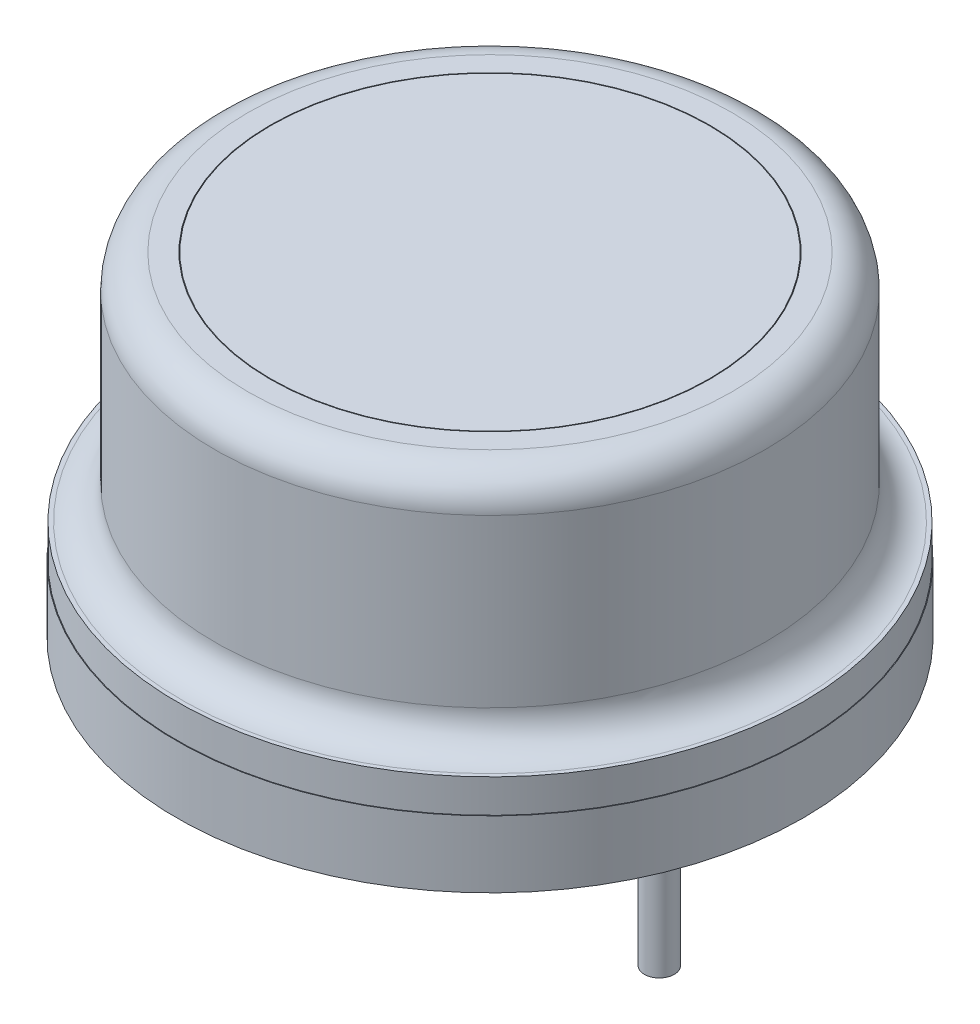
SolidWorks part; units mm, degrees
material "Stainless Steel (ferritic)"
ref_plane "Front" through (0, 0, 0) normal (0, 0, 1) x (1, 0, 0)
ref_plane "Top" through (0, 0, 0) normal (0, 1, 0) x (1, 0, 0)
ref_plane "Right" through (0, 0, 0) normal (1, 0, 0) x (0, 0, -1)
sketch "Sketch1" plane through (0, 0, 0) normal (0, 0, 1) x (1, 0, 0)
  line L0 (0, 0) -> (0, 4.4) construction
  line L1 (0, 4.4) -> (-3.3, 4.4)
  line L2 (-3.3, 4.4) -> (-3.3, 5)
  line L3 (-3.3, 5) -> (-3.63, 5)
  line L4 (-4.13, 4.5) -> (-4.13, 2)
  line L5 (-4.63, 1.5) -> (-4.69, 1.5)
  line L6 (-4.69, 1.5) -> (-4.69, 1)
  line L7 (-4.69, 1) -> (-4.7, 1)
  line L8 (-4.7, 1) -> (-4.7, 0)
  line L9 (-4.7, 0) -> (0, 0)
  line L10 (0, 0) -> (0, 4.4)
  arc A0 (-3.63, 5) -> (-4.13, 4.5) centre (-3.63, 4.5) ccw
  arc A1 (-4.13, 2) -> (-4.63, 1.5) centre (-4.63, 2) cw
  dimension "D7" = 0.5
  dimension "D10" = 0.5
  dimension "D1" = 0.01
  dimension "D2" = 6.6
  dimension "D3" = 8.26
  dimension "D4" = 9.4
  dimension "D5" = 5
  dimension "D6" = 0.6
  dimension "D8" = 0.5
  dimension "D9" = 1
revolve "Revolve1" add sketch "Sketch1" angle 360 about L0
sketch "Sketch2" plane through (0, 0, 0) normal (0, -1, 0) x (1, 0, 0)
  line L0 (-2.54, 0) -> (2.54, 0) construction
  circle A0 centre (-2.54, 0) radius 0.225
  circle A1 centre (2.54, 0) radius 0.225
  dimension "D1" = 0.45
  dimension "D2" = 5.08
extrude "Boss-Extrude1" add sketch "Sketch2" along normal blind 3 separate body
sketch "Sketch3" plane through (0, 0, 0) normal (0, 0, 1) x (1, 0, 0)
  line L0 (-3.29, 5) -> (-3.29, 4.41)
  line L1 (3.3, 5) -> (-3.3, 5) construction
  line L2 (-3.29, 4.41) -> (0, 4.41)
  line L3 (0, 4.41) -> (0, 5) construction
  line L4 (0, 5) -> (-3.29, 5)
  line L5 (3.3, 4.4) -> (-3.3, 4.4) construction
  line L6 (-3.3, 5) -> (-3.3, 4.4) construction
  line L7 (0, 4.41) -> (0, 5)
  dimension "D1" = 0.01
  dimension "D2" = 0.01
revolve "Revolve2" add sketch "Sketch3" angle 360 about L3
